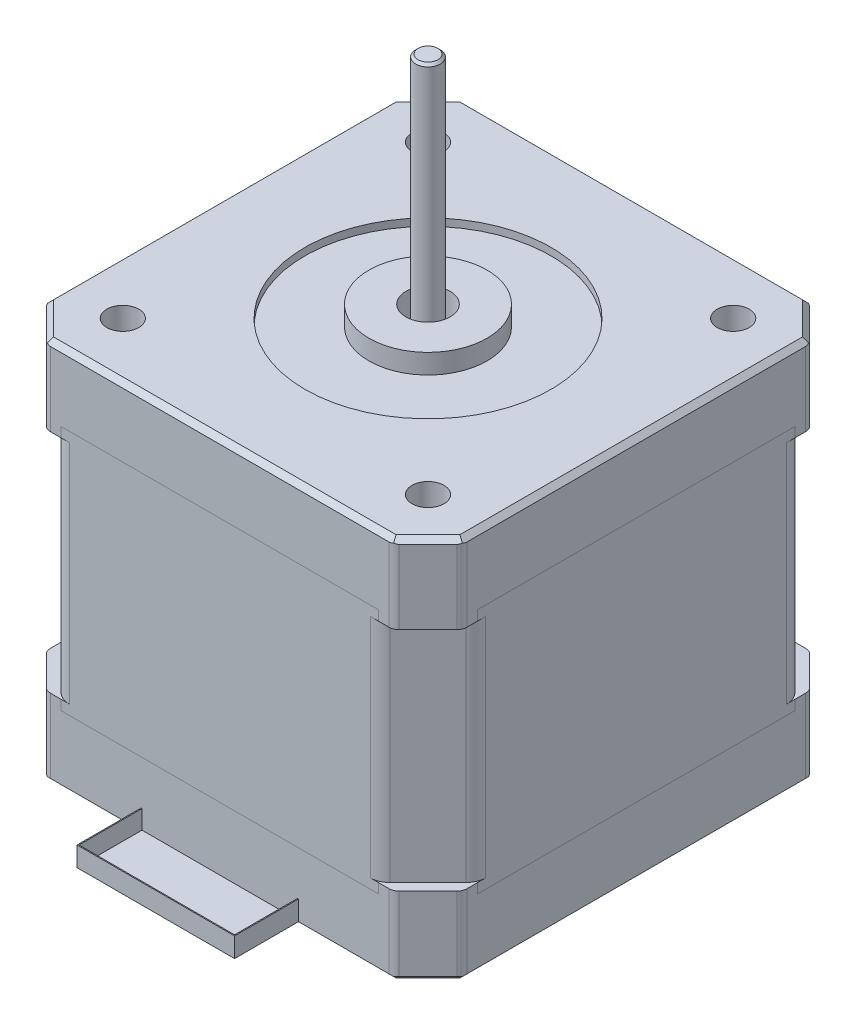
SolidWorks part; units mm, degrees
ref_plane "Front Plane" through (0, 0, 0) normal (0, 0, 1) x (1, 0, 0)
ref_plane "Top Plane" through (0, 0, 0) normal (0, 1, 0) x (1, 0, 0)
ref_plane "Right Plane" through (0, 0, 0) normal (1, 0, 0) x (0, 0, -1)
sketch "Sketch1" plane through (0, 0, 0) normal (0, 1, 0) x (1, 0, 0)
  line L0 (-41.2413, 0) -> (21.15, 0) construction
  line L1 (0, -27.9894) -> (0, 21.15) construction
  line L2 (-21.15, -17.6145) -> (-21.15, 17.6145)
  line L3 (-21.15, 17.6145) -> (-17.6145, 21.15)
  line L4 (-17.6145, 21.15) -> (17.6145, 21.15)
  line L5 (17.6145, 21.15) -> (21.15, 17.6145)
  line L6 (21.15, 17.6145) -> (21.15, -17.6145)
  line L7 (21.15, -17.6145) -> (17.6145, -21.15)
  line L8 (17.6145, -21.15) -> (-17.6145, -21.15)
  line L9 (-17.6145, -21.15) -> (-21.15, -17.6145)
  point P12 (21.15, 0.1284)
  point P14 (0, 21.2784)
  dimension "D1" = 42.3
  dimension "D2" = 45
  dimension "D3" = 5
extrude "Boss-Extrude1" add sketch "Sketch1" against normal blind 8
sketch "Sketch2" plane through (0, 0, 0) normal (0, 1, 0) x (1, 0, 0)
  line L0 (-21.15, 0) -> (21.15, 0) construction
  line L1 (-21.15, 17.6145) -> (-21.15, -17.6145) construction
  line L2 (21.15, -17.6145) -> (21.15, 17.6145) construction
  line L3 (0, -21.15) -> (0, 21.15) construction
  line L4 (-17.6145, -21.15) -> (17.6145, -21.15) construction
  line L5 (17.6145, 21.15) -> (-17.6145, 21.15) construction
  circle A0 centre (-15.5, 15.5) radius 1.6248
  circle A1 centre (15.5, 15.5) radius 1.6248
  circle A2 centre (15.5, -15.5) radius 1.6248
  circle A3 centre (-15.5, -15.5) radius 1.6248
  dimension "D1" = 31
  dimension "D2" = 31
extrude "Cut-Extrude1" cut sketch "Sketch2" against normal blind 6
chamfer "Chamfer1" distance 0.5 angle 45 8 edges at (-21.15, 0, 0) (-19.3822, 0, -19.3822) (0, 0, -21.15) (19.3822, 0, -19.3822) (21.15, 0, 0) (19.3822, 0, 19.3822) (0, 0, 21.15) (-19.3822, 0, 19.3822)
sketch "Sketch3" plane through (21.15, 0, 0) normal (1, 0, 0) x (0, 0, -1)
  line L0 (-16.1145, -8) -> (16.1145, -8)
  line L1 (-17.6145, -8) -> (17.6145, -8) construction
  line L2 (-16.1145, -8) -> (-16.1145, -7)
  line L3 (-16.1145, -7) -> (16.1145, -7)
  line L4 (16.1145, -7) -> (16.1145, -8)
  dimension "D1" = 1.5
  dimension "D2" = 1.5
  dimension "D3" = 1
extrude "Cut-Extrude2" cut sketch "Sketch3" against normal through all
sketch "Sketch4" plane through (0, 0, 21.15) normal (0, 0, 1) x (1, 0, 0)
  line L0 (-16.1145, -8) -> (-16.1145, -7)
  line L1 (-17.6145, -8) -> (17.6145, -8) construction
  line L2 (-16.1145, -7) -> (16.1145, -7)
  line L3 (16.1145, -7) -> (16.1145, -8)
  line L4 (16.1145, -8) -> (-16.1145, -8)
  line L5 (-17.6145, -8) -> (-17.6145, -0.5) construction
  line L6 (17.6145, -8) -> (17.6145, -0.5) construction
  dimension "D1" = 1.5
  dimension "D2" = 1.5
  dimension "D3" = 1
extrude "Cut-Extrude3" cut sketch "Sketch4" against normal through all
sketch "Sketch5" plane through (0, -8, 0) normal (0, -1, 0) x (1, 0, 0)
  line L0 (-21.15, 16.1145) -> (-16.1145, 21.15)
  line L4 (-21.15, 16.1145) -> (-16.1145, 16.1145)
  line L5 (-16.1145, 16.1145) -> (-16.1145, 21.15)
extrude "Cut-Extrude4" cut sketch "Sketch5" against normal blind 1
mirror "Mirror1" about plane through (0, 0, 0) normal (1, 0, 0) of "Cut-Extrude4"
mirror "Mirror2" about plane through (0, 0, 0) normal (0, 0, 1) of "Mirror1", "Cut-Extrude4"
sketch "Sketch6" plane through (0, -7, 0) normal (0, -1, 0) x (1, 0, 0)
  line L0 (-21.15, -16.1145) -> (-21.15, 16.1145)
  line L1 (-21.15, 16.1145) -> (-16.1145, 21.15)
  line L2 (-16.1145, 21.15) -> (16.1145, 21.15)
  line L3 (16.1145, 21.15) -> (21.15, 16.1145)
  line L4 (21.15, 16.1145) -> (21.15, -16.1145)
  line L5 (21.15, -16.1145) -> (16.1145, -21.15)
  line L6 (16.1145, -21.15) -> (-16.1145, -21.15)
  line L7 (-16.1145, -21.15) -> (-21.15, -16.1145)
extrude "Boss-Extrude2" add sketch "Sketch6" along normal blind 24
sketch "Sketch12" plane through (21.15, 0, 0) normal (1, 0, 0) x (0, 0, -1)
  line L0 (-16.1145, -8) -> (-16.1145, -7)
  line L1 (-16.1145, -7) -> (16.1145, -7)
  line L2 (16.1145, -7) -> (16.1145, -8)
  dimension "D1" = 1
split line "Split Line5"
sketch "Sketch13" plane through (0, 0, -21.15) normal (0, 0, -1) x (-1, 0, 0)
  line L0 (-16.1145, -8) -> (-16.1145, -7)
  line L1 (-16.1145, -7) -> (16.1145, -7)
  line L2 (16.1145, -7) -> (16.1145, -8)
  dimension "D1" = 1
split line "Split Line6"
sketch "Sketch14" plane through (-21.15, 0, 0) normal (-1, 0, 0) x (0, 0, 1)
  line L0 (-16.1145, -8) -> (-16.1145, -7)
  line L1 (-16.1145, -7) -> (16.1145, -7)
  line L2 (16.1145, -7) -> (16.1145, -8)
  dimension "D1" = 1
split line "Split Line7"
sketch "Sketch15" plane through (0, 0, 21.15) normal (0, 0, 1) x (1, 0, 0)
  line L0 (-16.1145, -8) -> (-16.1145, -7)
  line L1 (-16.1145, -7) -> (16.1145, -7)
  line L2 (16.1145, -7) -> (16.1145, -8)
  dimension "D1" = 1
split line "Split Line8"
sketch "Sketch16" plane through (0, -31, 0) normal (0, -1, 0) x (1, 0, 0)
  line L0 (-21.15, -17.6145) -> (-21.15, 17.6145)
  line L1 (-21.15, 17.6145) -> (-17.6145, 21.15)
  line L2 (-17.6145, 21.15) -> (17.6145, 21.15)
  line L3 (17.6145, 21.15) -> (21.15, 17.6145)
  line L4 (21.15, 17.6145) -> (21.15, -17.6145)
  line L5 (21.15, -17.6145) -> (17.6145, -21.15)
  line L6 (17.6145, -21.15) -> (-17.6145, -21.15)
  line L7 (-17.6145, -21.15) -> (-21.15, -17.6145)
extrude "Boss-Extrude4" add sketch "Sketch16" along normal blind 8
sketch "Sketch17" plane through (0, 0, 21.15) normal (0, 0, 1) x (1, 0, 0)
  line L0 (-16.1145, -31) -> (-16.1145, -32)
  line L1 (-16.1145, -32) -> (16.1145, -32)
  line L2 (16.1145, -32) -> (16.1145, -31)
  dimension "D1" = 1
split line "Split Line9"
sketch "Sketch18" plane through (21.15, 0, 0) normal (1, 0, 0) x (0, 0, -1)
  line L0 (-16.1145, -31) -> (-16.1145, -32)
  line L1 (-16.1145, -32) -> (16.1145, -32)
  line L2 (16.1145, -32) -> (16.1145, -31)
  dimension "D1" = 1
split line "Split Line10"
sketch "Sketch19" plane through (0, 0, -21.15) normal (0, 0, -1) x (-1, 0, 0)
  line L0 (-16.1145, -31) -> (-16.1145, -32)
  line L1 (-16.1145, -32) -> (16.1145, -32)
  line L2 (16.1145, -32) -> (16.1145, -31)
  dimension "D1" = 1
split line "Split Line11"
sketch "Sketch20" plane through (-21.15, 0, 0) normal (-1, 0, 0) x (0, 0, 1)
  line L0 (-16.1145, -31) -> (-16.1145, -32)
  line L1 (-16.1145, -32) -> (16.1145, -32)
  line L2 (16.1145, -32) -> (16.1145, -31)
  dimension "D1" = 1
split line "Split Line12"
sketch "Sketch22" plane through (0, 0, 21.15) normal (0, 0, 1) x (1, 0, 0)
  line L0 (-8, -39) -> (8, -39)
  line L1 (17.6145, -39) -> (-17.6145, -39) construction
  line L2 (8, -39) -> (8, -36.5)
  line L3 (8, -36.5) -> (-8, -36.5)
  line L4 (-8, -36.5) -> (-8, -39)
  line L5 (0, 0) -> (0, -39) construction
  dimension "D1" = 16
  dimension "D2" = 2.5
extrude "Boss-Extrude5" add sketch "Sketch22" along normal blind 6.5
chamfer "Chamfer3" distance 0.5 angle 45 12 edges at (-21.15, -39, 0) (-19.3822, -39, 19.3822) (-12.8072, -39, 21.15) (-8, -39, 24.4) (0, -39, 27.65) (8, -39, 24.4) (12.8072, -39, 21.15) (19.3822, -39, 19.3822) (21.15, -39, 0) (19.3822, -39, -19.3822) (0, -39, -21.15) (-19.3822, -39, -19.3822)
sketch "Sketch23" plane through (0, -36.5, 0) normal (0, 1, 0) x (1, 0, 0)
  line L0 (-8, -27.65) -> (-8, -21.15) construction
  line L1 (-7.9, -21.15) -> (7.9, -21.15)
  line L2 (-7.9, -21.15) -> (-7.9, -27.55)
  line L3 (-7.9, -27.55) -> (7.9, -27.55)
  line L4 (7.9, -21.15) -> (7.9, -27.55)
  line L5 (-7.9, -21.15) -> (7.9, -27.55) construction
  line L6 (-7.9, -27.55) -> (7.9, -21.15) construction
  line L7 (8, -27.65) -> (8, -21.15) construction
  line L8 (8, -27.65) -> (-8, -27.65) construction
  line L10 (8, -21.15) -> (-8, -21.15) construction
  point P0 (0, -24.35)
  dimension "D1" = 0.1
  dimension "D2" = 0.1
  dimension "D3" = 0.1
extrude "Cut-Extrude5" cut sketch "Sketch23" against normal blind 1.9
sketch "Sketch24" plane through (0, 0, 0) normal (0, 1, 0) x (1, 0, 0)
  circle A0 centre (0, 0) radius 12.5
  dimension "D1" = 25
extrude "Cut-Extrude6" cut sketch "Sketch24" against normal blind 0.75
sketch "Sketch25" plane through (0, -0.75, 0) normal (0, 1, 0) x (1, 0, 0)
  circle A0 centre (0, 0) radius 6
  dimension "D1" = 12
extrude "Boss-Extrude6" add sketch "Sketch25" along normal blind 2
sketch "Sketch26" plane through (0, 1.25, 0) normal (0, 1, 0) x (1, 0, 0)
  circle A0 centre (0, 0) radius 2.25
  dimension "D1" = 4.5
extrude "Cut-Extrude7" cut sketch "Sketch26" against normal blind 5
sketch "Sketch27" plane through (0, -3.75, 0) normal (0, 1, 0) x (1, 0, 0)
  circle A0 centre (0, 0) radius 1.2521
  dimension "D1" = 2.5041
extrude "Boss-Extrude7" add sketch "Sketch27" along normal blind 27
chamfer "Chamfer5" distance 0.25 angle 45 1 edges at (0, 23.25, 1.2521)
fillet "Fillet1" radius 2 8 edges at (-16.1145, -19.5, 21.15) (-21.15, -19.5, 16.1145) (-21.15, -19.5, -16.1145) (-16.1145, -19.5, -21.15) (21.15, -19.5, -16.1145) (16.1145, -19.5, -21.15) (21.15, -19.5, 16.1145) (16.1145, -19.5, 21.15)
fillet "Fillet3" radius 1 8 edges at (-17.6145, -4.25, 21.15) (-21.15, -4.25, 17.6145) (-21.15, -4.25, -17.6145) (-17.6145, -4.25, -21.15) (17.6145, -4.25, -21.15) (21.15, -4.25, -17.6145) (17.6145, -4.25, 21.15) (21.15, -4.25, 17.6145)
fillet "Fillet4" radius 1 8 edges at (-17.6145, -34.75, 21.15) (-21.15, -34.75, 17.6145) (-21.15, -34.75, -17.6145) (-17.6145, -34.75, -21.15) (17.6145, -34.75, -21.15) (21.15, -34.75, -17.6145) (21.15, -34.75, 17.6145) (17.6145, -34.75, 21.15)
